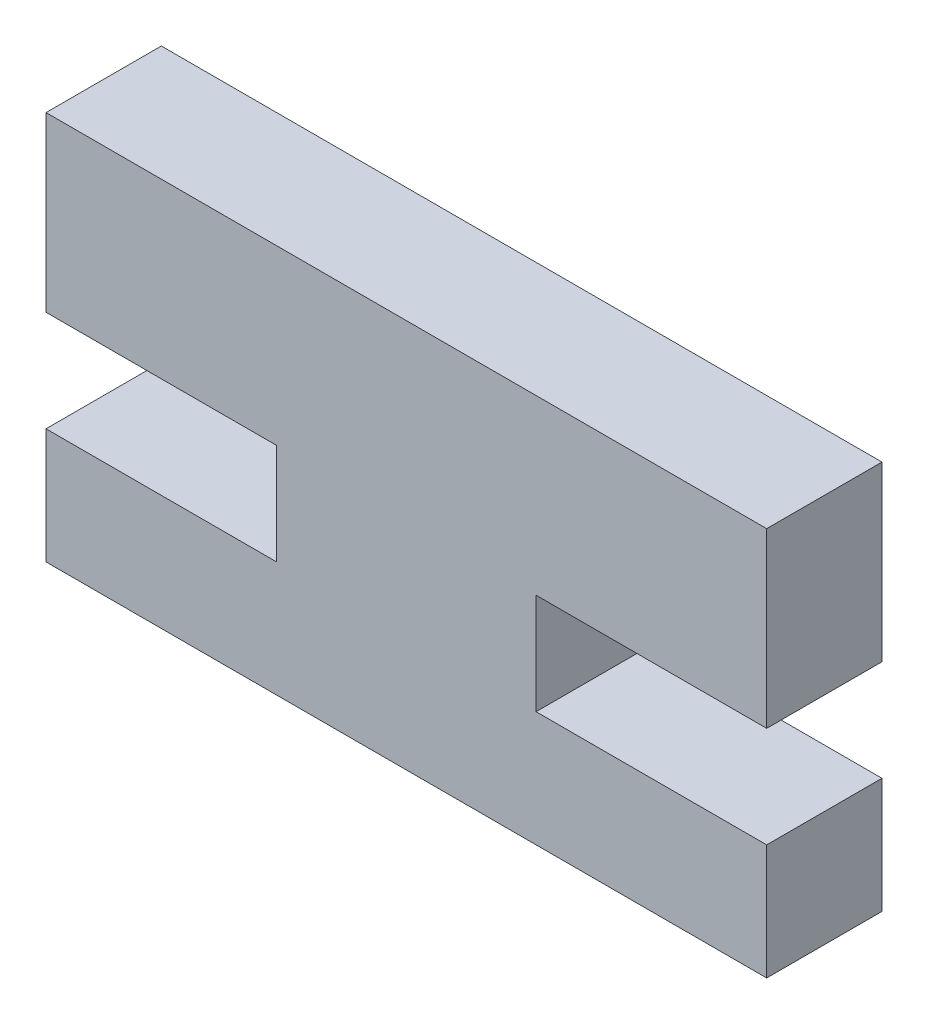
SolidWorks part; units mm, degrees
ref_plane "Front Plane" through (0, 0, 0) normal (0, 0, 1) x (1, 0, 0)
ref_plane "Top Plane" through (0, 0, 0) normal (0, 1, 0) x (1, 0, 0)
ref_plane "Right Plane" through (0, 0, 0) normal (1, 0, 0) x (0, 0, -1)
sketch "Sketch1" plane through (0, 0, 0) normal (0, 0, 1) x (1, 0, 0)
  line L0 (-68.1719, 24.3044) -> (-43.1719, 24.3044)
  line L1 (-60.1719, 18.3044) -> (-51.1719, 18.3044) construction
  line L2 (-68.1719, 24.3044) -> (-68.1719, 18.3044)
  line L3 (-68.1719, 18.3044) -> (-60.1719, 18.3044)
  line L5 (-68.1719, 14.8044) -> (-60.1719, 14.8044)
  line L6 (-68.1719, 14.8044) -> (-68.1719, 10.8044)
  line L7 (-68.1719, 10.8044) -> (-43.1719, 10.8044)
  line L10 (-60.1719, 18.3044) -> (-60.1719, 14.8044)
  line L12 (-51.1719, 18.3044) -> (-51.1719, 14.8044)
  line L13 (-51.1719, 18.3044) -> (-43.1719, 18.3044)
  line L16 (-43.1719, 18.3044) -> (-43.1719, 24.3044)
  line L17 (-51.1719, 14.8044) -> (-43.1719, 14.8044)
  line L20 (-43.1719, 14.8044) -> (-43.1719, 10.8044)
  dimension "D1" = 8
extrude "Boss-Extrude1" add sketch "Sketch1" along normal blind 4
